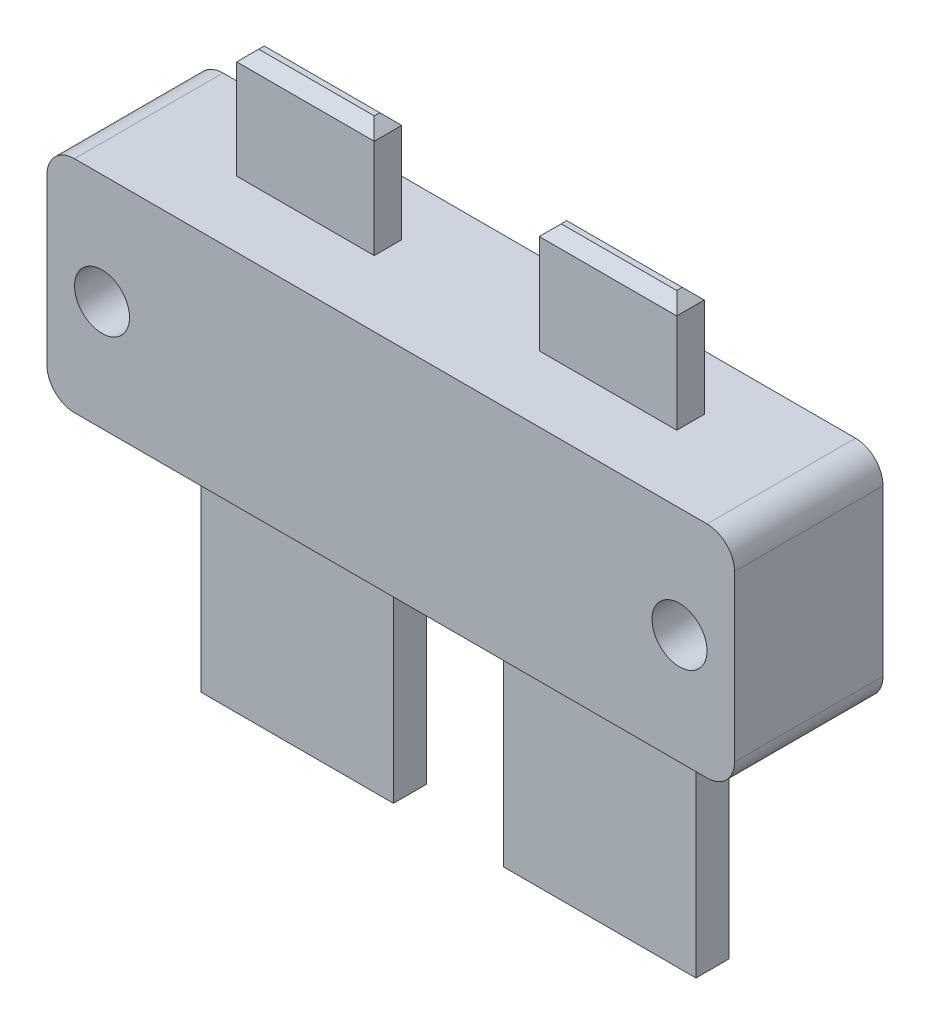
SolidWorks part; units mm, degrees
ref_plane "前视基准面" through (0, 0, 0) normal (0, 0, 1) x (1, 0, 0)
ref_plane "上视基准面" through (0, 0, 0) normal (0, 1, 0) x (1, 0, 0)
ref_plane "右视基准面" through (0, 0, 0) normal (1, 0, 0) x (0, 0, -1)
sketch "草图1" plane through (0, 0, 0) normal (0, 0, 1) x (1, 0, 0)
  line L1 (0, 0) -> (25, 0)
  line L2 (0, 0) -> (0, -8)
  line L3 (0, -8) -> (25, -8)
  line L4 (25, 0) -> (25, -8)
  dimension "D1" = 25
  dimension "D2" = 8
extrude "凸台-拉伸1" add sketch "草图1" along normal blind 5.4
sketch "草图2" plane through (0, -8, 0) normal (0, -1, 0) x (1, 0, 0)
  line L0 (0, 0) -> (25, 0) construction
  line L1 (3.5, 3.3) -> (10.5, 3.3)
  line L2 (3.5, 3.3) -> (3.5, 2.1)
  line L3 (3.5, 2.1) -> (10.5, 2.1)
  line L4 (10.5, 3.3) -> (10.5, 2.1)
  line L5 (14.5, 3.3) -> (21.5, 3.3)
  line L6 (14.5, 3.3) -> (14.5, 2.1)
  line L7 (14.5, 2.1) -> (21.5, 2.1)
  line L8 (21.5, 3.3) -> (21.5, 2.1)
  line L9 (0, 5.4) -> (0, 0) construction
  dimension "D1" = 1.2
  dimension "D2" = 1.2
  dimension "D3" = 7
  dimension "D4" = 7
  dimension "D5" = 4
  dimension "D6" = 2.1
  dimension "D7" = 3.5
extrude "凸台-拉伸2" add sketch "草图2" along normal blind 9
sketch "草图3" plane through (0, 0, 0) normal (0, 1, 0) x (1, 0, 0)
  line L0 (0, -5.4) -> (0, 0) construction
  line L1 (4.5, -2) -> (9.5, -2)
  line L2 (4.5, -2) -> (4.5, -3)
  line L3 (4.5, -3) -> (9.5, -3)
  line L4 (9.5, -2) -> (9.5, -3)
  line L5 (15.5, -2) -> (20.5, -2)
  line L6 (15.5, -2) -> (15.5, -3)
  line L7 (15.5, -3) -> (20.5, -3)
  line L8 (20.5, -2) -> (20.5, -3)
  line L9 (25, 0) -> (0, 0) construction
  dimension "D1" = 5
  dimension "D2" = 5
  dimension "D3" = 6
  dimension "D4" = 4.5
  dimension "D5" = 1
  dimension "D6" = 2
  dimension "D7" = 1
extrude "凸台-拉伸3" add sketch "草图3" along normal blind 4
chamfer "倒角2" distance 0.4 angle 45 7 edges at (4.5, 4, 2.5) (9.5, 4, 2.5) (15.5, 4, 2.5) (20.5, 4, 2.5) (21.5, -17, 2.7) (14.5, -17, 2.7) (10.5, -17, 2.7)
chamfer "倒角3" distance 0.4 angle 45 8 edges at (7, 4, 2) (7, 4, 3) (18, 4, 2) (18, 4, 3) (18, -17, 2.1) (18, -17, 3.3) (7, -17, 2.1) (7, -17, 3.3)
sketch "草图4" plane through (0, 0, 5.4) normal (0, 0, 1) x (1, 0, 0)
  line L0 (25, 0) -> (0, 0) construction
  line L1 (0, 0) -> (0, -8) construction
  circle A0 centre (2, -4) radius 1
  circle A1 centre (23, -4) radius 1
  dimension "D1" = 21
  dimension "D2" = 4
  dimension "D3" = 2
  dimension "D4" = 2
  dimension "D5" = 2
extrude "切除-拉伸1" cut sketch "草图4" against normal blind 2
fillet "圆角1" radius 1 4 edges at (0, 0, 2.7) (0, -8, 2.7) (25, 0, 2.7) (25, -8, 2.7)
